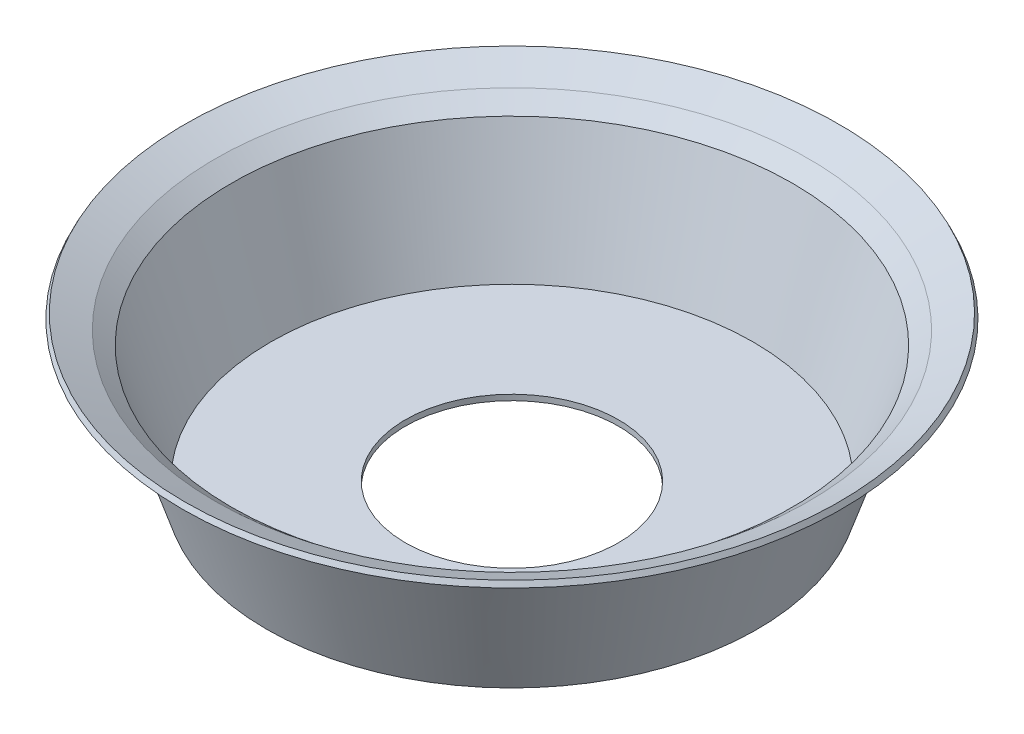
SolidWorks part; units mm, degrees
ref_plane "Спереди" through (0, 0, 0) normal (0, 0, 1) x (1, 0, 0)
ref_plane "Сверху" through (0, 0, 0) normal (0, 1, 0) x (1, 0, 0)
ref_plane "Справа" through (0, 0, 0) normal (1, 0, 0) x (0, 0, -1)
sketch "Эскиз1" plane through (0, 0, 0) normal (0, 0, 1) x (1, 0, 0)
  line L0 (0, 0) -> (0, -32.1034) construction
  line L1 (-5.6001, 0) -> (69.589, 0) construction
  line L2 (19, 0) -> (43, 0)
  line L3 (52.8896, 23.3322) -> (58.3028, 25.953)
  line L4 (50, 21) -> (43, 0)
  line L5 (50, 21) -> (52.8896, 23.3322)
revolve "Повернуть-Тонкостенный1" add sketch "Эскиз1" angle 360 about L0
